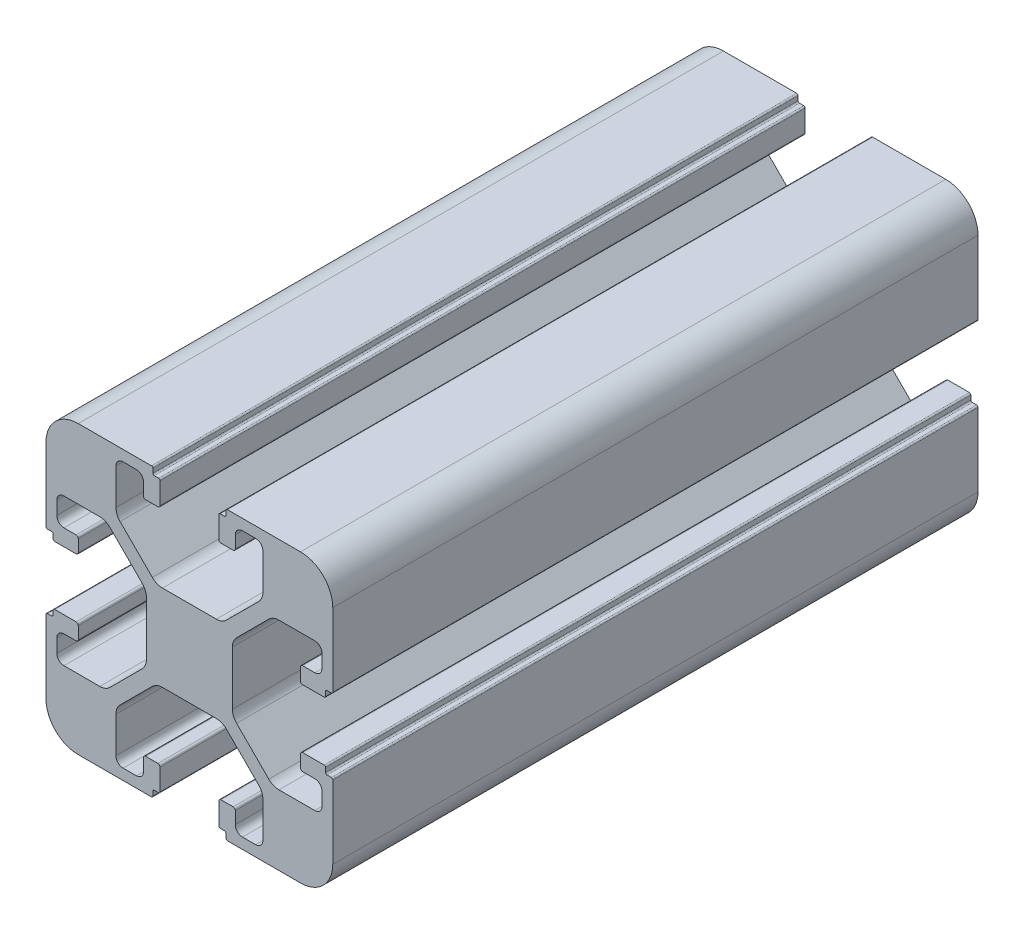
SolidWorks part; units mm, degrees
material "6063-T5"
ref_plane "Front Plane" through (0, 0, 0) normal (0, 0, 1) x (1, 0, 0)
ref_plane "Top Plane" through (0, 0, 0) normal (0, 1, 0) x (1, 0, 0)
ref_plane "Right Plane" through (0, 0, 0) normal (1, 0, 0) x (0, 0, -1)
sketch "Sketch2" plane through (0, 0, 0) normal (0, 0, 1) x (1, 0, 0)
  line L0 (4.5, 0) -> (14.7, 0)
  line L1 (40, 4.5) -> (40, 14.7)
  line L2 (35.5, 40) -> (25.3, 40)
  line L3 (0, 35.5) -> (0, 25.3)
  line L4 (15.9, 1.2) -> (15.9, 4.2)
  line L5 (24.1, 1.2) -> (24.1, 4.2)
  line L6 (38.8, 24.1) -> (35.8, 24.1)
  line L7 (35.5, 24.4) -> (35.5, 26.1)
  line L8 (14, 23.7574) -> (14, 16.2426)
  line L9 (16.2426, 14) -> (23.7574, 14)
  line L10 (26, 16.2426) -> (26, 23.7574)
  line L11 (13.4142, 14.8284) -> (8.9216, 10.3358)
  line L12 (23.7574, 26) -> (16.2426, 26)
  line L13 (4.5, 24.4) -> (4.5, 26.1)
  line L14 (1.2, 24.1) -> (4.2, 24.1)
  line L15 (15.9, 38.8) -> (15.9, 35.8)
  line L16 (14.8284, 26.5858) -> (10.3358, 31.0784)
  line L17 (13.4142, 25.1716) -> (8.9216, 29.6642)
  line L18 (14.8284, 13.4142) -> (10.3358, 8.9216)
  line L19 (25.1716, 13.4142) -> (29.6642, 8.9216)
  line L20 (26.5858, 14.8284) -> (31.0784, 10.3358)
  line L21 (26.5858, 25.1716) -> (31.0784, 29.6642)
  line L22 (25.1716, 26.5858) -> (29.6642, 31.0784)
  line L23 (24.1, 38.8) -> (24.1, 35.8)
  line L24 (14.7, 40) -> (4.5, 40)
  line L25 (25.3, 0) -> (35.5, 0)
  line L26 (38.8, 15.9) -> (35.8, 15.9)
  line L27 (40, 25.3) -> (40, 35.5)
  line L28 (1.2, 15.9) -> (4.2, 15.9)
  line L29 (0, 14.7) -> (0, 4.5)
  line L30 (4.5, 15.6) -> (4.5, 13.9)
  line L31 (35.5, 15.6) -> (35.5, 13.9)
  line L32 (15.6, 35.5) -> (13.9, 35.5)
  line L33 (24.4, 35.5) -> (26.1, 35.5)
  line L34 (15.6, 4.5) -> (13.9, 4.5)
  line L35 (24.4, 4.5) -> (26.1, 4.5)
  line L36 (12.6, 38.5) -> (10.75, 38.5)
  line L37 (1.5, 12.6) -> (1.5, 10.75)
  line L38 (27.4, 1.5) -> (29.25, 1.5)
  line L39 (38.5, 27.4) -> (38.5, 29.25)
  line L40 (38.5, 10.75) -> (38.5, 12.6)
  line L41 (29.25, 38.5) -> (27.4, 38.5)
  line L42 (1.5, 29.25) -> (1.5, 27.4)
  line L43 (10.75, 1.5) -> (12.6, 1.5)
  line L44 (35.8, 26.4) -> (37.5, 26.4)
  line L45 (35.8, 13.6) -> (37.5, 13.6)
  line L46 (4.2, 26.4) -> (2.5, 26.4)
  line L47 (13.6, 35.8) -> (13.6, 37.5)
  line L48 (26.4, 35.8) -> (26.4, 37.5)
  line L49 (4.2, 13.6) -> (2.5, 13.6)
  line L50 (13.6, 4.2) -> (13.6, 2.5)
  line L51 (26.4, 4.2) -> (26.4, 2.5)
  line L52 (9.75, 7.5074) -> (9.75, 2.5)
  line L53 (30.25, 7.5074) -> (30.25, 2.5)
  line L54 (9.75, 37.5) -> (9.75, 32.4926)
  line L55 (30.25, 37.5) -> (30.25, 32.4926)
  line L56 (32.4926, 30.25) -> (37.5, 30.25)
  line L57 (37.5, 9.75) -> (32.4926, 9.75)
  line L58 (2.5, 30.25) -> (7.5074, 30.25)
  line L59 (2.5, 9.75) -> (7.5074, 9.75)
  line L60 (31.55, 37.7) -> (31.55, 32.55)
  line L61 (32.55, 31.55) -> (37.7, 31.55)
  line L62 (1.3, 35.5) -> (1.3, 32.55)
  line L63 (4.5, 38.7) -> (7.45, 38.7)
  line L64 (32.55, 38.7) -> (35.5, 38.7)
  line L65 (38.7, 35.5) -> (38.7, 32.55)
  line L66 (8.45, 37.7) -> (8.45, 32.55)
  line L67 (2.3, 31.55) -> (7.45, 31.55)
  line L68 (1.3, 7.45) -> (1.3, 4.5)
  line L69 (2.3, 8.45) -> (7.45, 8.45)
  line L70 (8.45, 7.45) -> (8.45, 2.3)
  line L71 (4.5, 1.3) -> (7.45, 1.3)
  line L72 (31.55, 7.45) -> (31.55, 2.3)
  line L73 (32.55, 8.45) -> (37.7, 8.45)
  line L74 (38.7, 7.45) -> (38.7, 4.5)
  line L75 (32.55, 1.3) -> (35.5, 1.3)
  line L77 (14.9, 39.8) -> (14.9, 39.2)
  line L78 (15.1, 39) -> (15.7, 39)
  line L79 (25.1, 39.8) -> (25.1, 39.2)
  line L80 (24.9, 39) -> (24.3, 39)
  line L81 (25.1, 0.2) -> (25.1, 0.8)
  line L82 (24.9, 1) -> (24.3, 1)
  line L83 (14.9, 0.2) -> (14.9, 0.8)
  line L84 (15.1, 1) -> (15.7, 1)
  line L85 (0.2, 25.1) -> (0.8, 25.1)
  line L86 (1, 24.9) -> (1, 24.3)
  line L87 (0.2, 14.9) -> (0.8, 14.9)
  line L88 (1, 15.1) -> (1, 15.7)
  line L89 (39.8, 25.1) -> (39.2, 25.1)
  line L90 (39, 24.9) -> (39, 24.3)
  line L91 (39, 15.7) -> (39, 15.1)
  line L92 (39.2, 14.9) -> (39.8, 14.9)
  circle A0 centre (20, 20) radius 3.4
  arc A1 (1.3, 35.5) -> (4.5, 38.7) centre (4.5, 35.5) cw
  arc A2 (1.3, 4.5) -> (4.5, 1.3) centre (4.5, 4.5) ccw
  arc A3 (38.7, 4.5) -> (35.5, 1.3) centre (35.5, 4.5) cw
  arc A4 (35.5, 38.7) -> (38.7, 35.5) centre (35.5, 35.5) cw
  arc A5 (40, 35.5) -> (35.5, 40) centre (35.5, 35.5) ccw
  arc A6 (35.5, 0) -> (40, 4.5) centre (35.5, 4.5) ccw
  arc A7 (4.5, 0) -> (0, 4.5) centre (4.5, 4.5) cw
  arc A8 (4.5, 40) -> (0, 35.5) centre (4.5, 35.5) ccw
  arc A9 (13.4142, 14.8284) -> (14, 16.2426) centre (12, 16.2426) ccw
  arc A10 (7.5074, 9.75) -> (8.9216, 10.3358) centre (7.5074, 11.75) ccw
  arc A11 (9.75, 7.5074) -> (10.3358, 8.9216) centre (11.75, 7.5074) cw
  arc A12 (30.25, 7.5074) -> (29.6642, 8.9216) centre (28.25, 7.5074) ccw
  arc A13 (14.8284, 13.4142) -> (16.2426, 14) centre (16.2426, 12) cw
  arc A14 (25.1716, 13.4142) -> (23.7574, 14) centre (23.7574, 12) ccw
  arc A15 (32.4926, 9.75) -> (31.0784, 10.3358) centre (32.4926, 11.75) cw
  arc A16 (26.5858, 14.8284) -> (26, 16.2426) centre (28, 16.2426) cw
  arc A17 (32.4926, 30.25) -> (31.0784, 29.6642) centre (32.4926, 28.25) ccw
  arc A18 (26.5858, 25.1716) -> (26, 23.7574) centre (28, 23.7574) ccw
  arc A19 (13.4142, 25.1716) -> (14, 23.7574) centre (12, 23.7574) cw
  arc A20 (7.5074, 30.25) -> (8.9216, 29.6642) centre (7.5074, 28.25) cw
  arc A21 (9.75, 32.4926) -> (10.3358, 31.0784) centre (11.75, 32.4926) ccw
  arc A22 (30.25, 32.4926) -> (29.6642, 31.0784) centre (28.25, 32.4926) cw
  arc A23 (25.1716, 26.5858) -> (23.7574, 26) centre (23.7574, 28) cw
  arc A24 (14.8284, 26.5858) -> (16.2426, 26) centre (16.2426, 28) ccw
  arc A25 (37.7, 8.45) -> (38.7, 7.45) centre (37.7, 7.45) cw
  arc A26 (31.55, 2.3) -> (32.55, 1.3) centre (32.55, 2.3) ccw
  arc A27 (31.55, 7.45) -> (32.55, 8.45) centre (32.55, 7.45) cw
  arc A28 (8.45, 2.3) -> (7.45, 1.3) centre (7.45, 2.3) cw
  arc A29 (1.3, 7.45) -> (2.3, 8.45) centre (2.3, 7.45) cw
  arc A30 (7.45, 8.45) -> (8.45, 7.45) centre (7.45, 7.45) cw
  arc A31 (38.7, 32.55) -> (37.7, 31.55) centre (37.7, 32.55) cw
  arc A32 (31.55, 32.55) -> (32.55, 31.55) centre (32.55, 32.55) ccw
  arc A33 (31.55, 37.7) -> (32.55, 38.7) centre (32.55, 37.7) cw
  arc A34 (7.45, 38.7) -> (8.45, 37.7) centre (7.45, 37.7) cw
  arc A35 (8.45, 32.55) -> (7.45, 31.55) centre (7.45, 32.55) cw
  arc A36 (1.3, 32.55) -> (2.3, 31.55) centre (2.3, 32.55) ccw
  arc A37 (30.25, 2.5) -> (29.25, 1.5) centre (29.25, 2.5) cw
  arc A38 (26.4, 2.5) -> (27.4, 1.5) centre (27.4, 2.5) ccw
  arc A39 (13.6, 2.5) -> (12.6, 1.5) centre (12.6, 2.5) cw
  arc A40 (9.75, 2.5) -> (10.75, 1.5) centre (10.75, 2.5) ccw
  arc A41 (26.4, 37.5) -> (27.4, 38.5) centre (27.4, 37.5) cw
  arc A42 (30.25, 37.5) -> (29.25, 38.5) centre (29.25, 37.5) ccw
  arc A43 (37.5, 26.4) -> (38.5, 27.4) centre (37.5, 27.4) ccw
  arc A44 (37.5, 30.25) -> (38.5, 29.25) centre (37.5, 29.25) cw
  arc A45 (37.5, 13.6) -> (38.5, 12.6) centre (37.5, 12.6) cw
  arc A46 (37.5, 9.75) -> (38.5, 10.75) centre (37.5, 10.75) ccw
  arc A47 (2.5, 9.75) -> (1.5, 10.75) centre (2.5, 10.75) cw
  arc A48 (2.5, 13.6) -> (1.5, 12.6) centre (2.5, 12.6) ccw
  arc A49 (2.5, 26.4) -> (1.5, 27.4) centre (2.5, 27.4) cw
  arc A50 (2.5, 30.25) -> (1.5, 29.25) centre (2.5, 29.25) ccw
  arc A51 (9.75, 37.5) -> (10.75, 38.5) centre (10.75, 37.5) cw
  arc A52 (13.6, 37.5) -> (12.6, 38.5) centre (12.6, 37.5) ccw
  arc A53 (26.1, 35.5) -> (26.4, 35.8) centre (26.1, 35.8) ccw
  arc A54 (24.1, 35.8) -> (24.4, 35.5) centre (24.4, 35.8) ccw
  arc A55 (15.9, 35.8) -> (15.6, 35.5) centre (15.6, 35.8) cw
  arc A56 (13.9, 35.5) -> (13.6, 35.8) centre (13.9, 35.8) cw
  arc A57 (13.9, 4.5) -> (13.6, 4.2) centre (13.9, 4.2) ccw
  arc A58 (15.9, 4.2) -> (15.6, 4.5) centre (15.6, 4.2) ccw
  arc A59 (24.1, 4.2) -> (24.4, 4.5) centre (24.4, 4.2) cw
  arc A60 (26.1, 4.5) -> (26.4, 4.2) centre (26.1, 4.2) cw
  arc A61 (35.5, 13.9) -> (35.8, 13.6) centre (35.8, 13.9) ccw
  arc A62 (35.8, 15.9) -> (35.5, 15.6) centre (35.8, 15.6) ccw
  arc A63 (35.8, 24.1) -> (35.5, 24.4) centre (35.8, 24.4) cw
  arc A64 (35.5, 26.1) -> (35.8, 26.4) centre (35.8, 26.1) cw
  arc A65 (4.5, 13.9) -> (4.2, 13.6) centre (4.2, 13.9) cw
  arc A66 (4.2, 15.9) -> (4.5, 15.6) centre (4.2, 15.6) cw
  arc A67 (4.2, 24.1) -> (4.5, 24.4) centre (4.2, 24.4) ccw
  arc A68 (4.5, 26.1) -> (4.2, 26.4) centre (4.2, 26.1) ccw
  arc A69 (25.3, 0) -> (25.1, 0.2) centre (25.3, 0.2) cw
  arc A70 (25.1, 0.8) -> (24.9, 1) centre (24.9, 0.8) ccw
  arc A71 (24.3, 1) -> (24.1, 1.2) centre (24.3, 1.2) cw
  arc A72 (14.7, 0) -> (14.9, 0.2) centre (14.7, 0.2) ccw
  arc A73 (14.9, 0.8) -> (15.1, 1) centre (15.1, 0.8) cw
  arc A74 (15.7, 1) -> (15.9, 1.2) centre (15.7, 1.2) ccw
  arc A75 (39.8, 14.9) -> (40, 14.7) centre (39.8, 14.7) cw
  arc A76 (39, 15.1) -> (39.2, 14.9) centre (39.2, 15.1) ccw
  arc A77 (38.8, 15.9) -> (39, 15.7) centre (38.8, 15.7) cw
  arc A78 (0, 25.3) -> (0.2, 25.1) centre (0.2, 25.3) ccw
  arc A79 (0.8, 25.1) -> (1, 24.9) centre (0.8, 24.9) cw
  arc A80 (1, 24.3) -> (1.2, 24.1) centre (1.2, 24.3) ccw
  arc A81 (0, 14.7) -> (0.2, 14.9) centre (0.2, 14.7) cw
  arc A82 (0.8, 14.9) -> (1, 15.1) centre (0.8, 15.1) ccw
  arc A83 (1, 15.7) -> (1.2, 15.9) centre (1.2, 15.7) cw
  arc A84 (39, 24.3) -> (38.8, 24.1) centre (38.8, 24.3) cw
  arc A85 (39.2, 25.1) -> (39, 24.9) centre (39.2, 24.9) ccw
  arc A86 (40, 25.3) -> (39.8, 25.1) centre (39.8, 25.3) cw
  arc A87 (24.3, 39) -> (24.1, 38.8) centre (24.3, 38.8) ccw
  arc A88 (25.1, 39.2) -> (24.9, 39) centre (24.9, 39.2) cw
  arc A89 (25.3, 40) -> (25.1, 39.8) centre (25.3, 39.8) ccw
  arc A90 (14.9, 39.2) -> (15.1, 39) centre (15.1, 39.2) ccw
  arc A91 (15.7, 39) -> (15.9, 38.8) centre (15.7, 38.8) cw
  arc A92 (14.7, 40) -> (14.9, 39.8) centre (14.7, 39.8) cw
  point P93 (0, 0)
extrude "Boss-Extrude1" add sketch "Sketch2" along normal blind 50
sketch "Sketch3" plane through (0, 0, 50) normal (0, 0, 1) x (1, 0, 0)
  line L76 (25.3, 0) -> (35.5, 0)
  line L77 (40, 4.5) -> (40, 14.7)
  line L78 (39.8, 14.9) -> (39.2, 14.9)
  line L79 (39, 15.1) -> (39, 15.7)
  line L80 (38.8, 15.9) -> (35.8, 15.9)
  line L81 (35.5, 15.6) -> (35.5, 13.9)
  line L82 (35.8, 13.6) -> (37.5, 13.6)
  line L83 (38.5, 12.6) -> (38.5, 10.75)
  line L84 (37.5, 9.75) -> (32.4926, 9.75)
  line L85 (31.0784, 10.3358) -> (26.5858, 14.8284)
  line L86 (26, 16.2426) -> (26, 23.7574)
  line L87 (26.5858, 25.1716) -> (31.0784, 29.6642)
  line L88 (32.4926, 30.25) -> (37.5, 30.25)
  line L89 (38.5, 29.25) -> (38.5, 27.4)
  line L90 (37.5, 26.4) -> (35.8, 26.4)
  line L91 (35.5, 26.1) -> (35.5, 24.4)
  line L92 (35.8, 24.1) -> (38.8, 24.1)
  line L93 (39, 24.3) -> (39, 24.9)
  line L94 (39.2, 25.1) -> (39.8, 25.1)
  line L95 (40, 25.3) -> (40, 35.5)
  line L96 (35.5, 40) -> (25.3, 40)
  line L97 (25.1, 39.8) -> (25.1, 39.2)
  line L98 (24.9, 39) -> (24.3, 39)
  line L99 (24.1, 38.8) -> (24.1, 35.8)
  line L100 (24.4, 35.5) -> (26.1, 35.5)
  line L101 (26.4, 35.8) -> (26.4, 37.5)
  line L102 (27.4, 38.5) -> (29.25, 38.5)
  line L103 (30.25, 37.5) -> (30.25, 32.4926)
  line L104 (29.6642, 31.0784) -> (25.1716, 26.5858)
  line L105 (23.7574, 26) -> (16.2426, 26)
  line L106 (14.8284, 26.5858) -> (10.3358, 31.0784)
  line L107 (9.75, 32.4926) -> (9.75, 37.5)
  line L108 (10.75, 38.5) -> (12.6, 38.5)
  line L109 (13.6, 37.5) -> (13.6, 35.8)
  line L110 (13.9, 35.5) -> (15.6, 35.5)
  line L111 (15.9, 35.8) -> (15.9, 38.8)
  line L112 (15.7, 39) -> (15.1, 39)
  line L113 (14.9, 39.2) -> (14.9, 39.8)
  line L114 (14.7, 40) -> (4.5, 40)
  line L115 (0, 35.5) -> (0, 25.3)
  line L116 (0.2, 25.1) -> (0.8, 25.1)
  line L117 (1, 24.9) -> (1, 24.3)
  line L118 (1.2, 24.1) -> (4.2, 24.1)
  line L119 (4.5, 24.4) -> (4.5, 26.1)
  line L120 (4.2, 26.4) -> (2.5, 26.4)
  line L121 (1.5, 27.4) -> (1.5, 29.25)
  line L122 (2.5, 30.25) -> (7.5074, 30.25)
  line L123 (8.9216, 29.6642) -> (13.4142, 25.1716)
  line L124 (14, 23.7574) -> (14, 16.2426)
  line L125 (13.4142, 14.8284) -> (8.9216, 10.3358)
  line L126 (7.5074, 9.75) -> (2.5, 9.75)
  line L127 (1.5, 10.75) -> (1.5, 12.6)
  line L128 (2.5, 13.6) -> (4.2, 13.6)
  line L129 (4.5, 13.9) -> (4.5, 15.6)
  line L130 (4.2, 15.9) -> (1.2, 15.9)
  line L131 (1, 15.7) -> (1, 15.1)
  line L132 (0.8, 14.9) -> (0.2, 14.9)
  line L133 (0, 14.7) -> (0, 4.5)
  line L134 (4.5, 0) -> (14.7, 0)
  line L135 (14.9, 0.2) -> (14.9, 0.8)
  line L136 (15.1, 1) -> (15.7, 1)
  line L137 (15.9, 1.2) -> (15.9, 4.2)
  line L138 (15.6, 4.5) -> (13.9, 4.5)
  line L139 (13.6, 4.2) -> (13.6, 2.5)
  line L140 (12.6, 1.5) -> (10.75, 1.5)
  line L141 (9.75, 2.5) -> (9.75, 7.5074)
  line L142 (10.3358, 8.9216) -> (14.8284, 13.4142)
  line L143 (16.2426, 14) -> (23.7574, 14)
  line L144 (25.1716, 13.4142) -> (29.6642, 8.9216)
  line L145 (30.25, 7.5074) -> (30.25, 2.5)
  line L146 (29.25, 1.5) -> (27.4, 1.5)
  line L147 (26.4, 2.5) -> (26.4, 4.2)
  line L148 (26.1, 4.5) -> (24.4, 4.5)
  line L149 (24.1, 4.2) -> (24.1, 1.2)
  line L150 (24.3, 1) -> (24.9, 1)
  line L151 (25.1, 0.8) -> (25.1, 0.2)
  line L152 (25.3, 0) -> (35.5, 0)
  line L153 (40, 4.5) -> (40, 14.7)
  line L154 (39.8, 14.9) -> (39.2, 14.9)
  line L155 (39, 15.1) -> (39, 15.7)
  line L156 (38.8, 15.9) -> (35.8, 15.9)
  line L157 (35.5, 15.6) -> (35.5, 13.9)
  line L158 (35.8, 13.6) -> (37.5, 13.6)
  line L159 (38.5, 12.6) -> (38.5, 10.75)
  line L160 (37.5, 9.75) -> (32.4926, 9.75)
  line L161 (31.0784, 10.3358) -> (26.5858, 14.8284)
  line L162 (26, 16.2426) -> (26, 23.7574)
  line L163 (26.5858, 25.1716) -> (31.0784, 29.6642)
  line L164 (32.4926, 30.25) -> (37.5, 30.25)
  line L165 (38.5, 29.25) -> (38.5, 27.4)
  line L166 (37.5, 26.4) -> (35.8, 26.4)
  line L167 (35.5, 26.1) -> (35.5, 24.4)
  line L168 (35.8, 24.1) -> (38.8, 24.1)
  line L169 (39, 24.3) -> (39, 24.9)
  line L170 (39.2, 25.1) -> (39.8, 25.1)
  line L171 (40, 25.3) -> (40, 35.5)
  line L172 (35.5, 40) -> (25.3, 40)
  line L173 (25.1, 39.8) -> (25.1, 39.2)
  line L174 (24.9, 39) -> (24.3, 39)
  line L175 (24.1, 38.8) -> (24.1, 35.8)
  line L176 (24.4, 35.5) -> (26.1, 35.5)
  line L177 (26.4, 35.8) -> (26.4, 37.5)
  line L178 (27.4, 38.5) -> (29.25, 38.5)
  line L179 (30.25, 37.5) -> (30.25, 32.4926)
  line L180 (29.6642, 31.0784) -> (25.1716, 26.5858)
  line L181 (23.7574, 26) -> (16.2426, 26)
  line L182 (14.8284, 26.5858) -> (10.3358, 31.0784)
  line L183 (9.75, 32.4926) -> (9.75, 37.5)
  line L184 (10.75, 38.5) -> (12.6, 38.5)
  line L185 (13.6, 37.5) -> (13.6, 35.8)
  line L186 (13.9, 35.5) -> (15.6, 35.5)
  line L187 (15.9, 35.8) -> (15.9, 38.8)
  line L188 (15.7, 39) -> (15.1, 39)
  line L189 (14.9, 39.2) -> (14.9, 39.8)
  line L190 (14.7, 40) -> (4.5, 40)
  line L191 (0, 35.5) -> (0, 25.3)
  line L192 (0.2, 25.1) -> (0.8, 25.1)
  line L193 (1, 24.9) -> (1, 24.3)
  line L194 (1.2, 24.1) -> (4.2, 24.1)
  line L195 (4.5, 24.4) -> (4.5, 26.1)
  line L196 (4.2, 26.4) -> (2.5, 26.4)
  line L197 (1.5, 27.4) -> (1.5, 29.25)
  line L198 (2.5, 30.25) -> (7.5074, 30.25)
  line L199 (8.9216, 29.6642) -> (13.4142, 25.1716)
  line L200 (14, 23.7574) -> (14, 16.2426)
  line L201 (13.4142, 14.8284) -> (8.9216, 10.3358)
  line L202 (7.5074, 9.75) -> (2.5, 9.75)
  line L203 (1.5, 10.75) -> (1.5, 12.6)
  line L204 (2.5, 13.6) -> (4.2, 13.6)
  line L205 (4.5, 13.9) -> (4.5, 15.6)
  line L206 (4.2, 15.9) -> (1.2, 15.9)
  line L207 (1, 15.7) -> (1, 15.1)
  line L208 (0.8, 14.9) -> (0.2, 14.9)
  line L209 (0, 14.7) -> (0, 4.5)
  line L210 (4.5, 0) -> (14.7, 0)
  line L211 (14.9, 0.2) -> (14.9, 0.8)
  line L212 (15.1, 1) -> (15.7, 1)
  line L213 (15.9, 1.2) -> (15.9, 4.2)
  line L214 (15.6, 4.5) -> (13.9, 4.5)
  line L215 (13.6, 4.2) -> (13.6, 2.5)
  line L216 (12.6, 1.5) -> (10.75, 1.5)
  line L217 (9.75, 2.5) -> (9.75, 7.5074)
  line L218 (10.3358, 8.9216) -> (14.8284, 13.4142)
  line L219 (16.2426, 14) -> (23.7574, 14)
  line L220 (25.1716, 13.4142) -> (29.6642, 8.9216)
  line L221 (30.25, 7.5074) -> (30.25, 2.5)
  line L222 (29.25, 1.5) -> (27.4, 1.5)
  line L223 (26.4, 2.5) -> (26.4, 4.2)
  line L224 (26.1, 4.5) -> (24.4, 4.5)
  line L225 (24.1, 4.2) -> (24.1, 1.2)
  line L226 (24.3, 1) -> (24.9, 1)
  line L227 (25.1, 0.8) -> (25.1, 0.2)
  arc A76 (25.1, 0.2) -> (25.3, 0) centre (25.3, 0.2) ccw
  arc A77 (35.5, 0) -> (40, 4.5) centre (35.5, 4.5) ccw
  arc A78 (40, 14.7) -> (39.8, 14.9) centre (39.8, 14.7) ccw
  arc A79 (39, 15.1) -> (39.2, 14.9) centre (39.2, 15.1) ccw
  arc A80 (39, 15.7) -> (38.8, 15.9) centre (38.8, 15.7) ccw
  arc A81 (35.8, 15.9) -> (35.5, 15.6) centre (35.8, 15.6) ccw
  arc A82 (35.5, 13.9) -> (35.8, 13.6) centre (35.8, 13.9) ccw
  arc A83 (38.5, 12.6) -> (37.5, 13.6) centre (37.5, 12.6) ccw
  arc A84 (37.5, 9.75) -> (38.5, 10.75) centre (37.5, 10.75) ccw
  arc A85 (31.0784, 10.3358) -> (32.4926, 9.75) centre (32.4926, 11.75) ccw
  arc A86 (26, 16.2426) -> (26.5858, 14.8284) centre (28, 16.2426) ccw
  arc A87 (26.5858, 25.1716) -> (26, 23.7574) centre (28, 23.7574) ccw
  arc A88 (32.4926, 30.25) -> (31.0784, 29.6642) centre (32.4926, 28.25) ccw
  arc A89 (38.5, 29.25) -> (37.5, 30.25) centre (37.5, 29.25) ccw
  arc A90 (37.5, 26.4) -> (38.5, 27.4) centre (37.5, 27.4) ccw
  arc A91 (35.8, 26.4) -> (35.5, 26.1) centre (35.8, 26.1) ccw
  arc A92 (35.5, 24.4) -> (35.8, 24.1) centre (35.8, 24.4) ccw
  arc A93 (38.8, 24.1) -> (39, 24.3) centre (38.8, 24.3) ccw
  arc A94 (39.2, 25.1) -> (39, 24.9) centre (39.2, 24.9) ccw
  arc A95 (39.8, 25.1) -> (40, 25.3) centre (39.8, 25.3) ccw
  arc A96 (40, 35.5) -> (35.5, 40) centre (35.5, 35.5) ccw
  arc A97 (25.3, 40) -> (25.1, 39.8) centre (25.3, 39.8) ccw
  arc A98 (24.9, 39) -> (25.1, 39.2) centre (24.9, 39.2) ccw
  arc A99 (24.3, 39) -> (24.1, 38.8) centre (24.3, 38.8) ccw
  arc A100 (24.1, 35.8) -> (24.4, 35.5) centre (24.4, 35.8) ccw
  arc A101 (26.1, 35.5) -> (26.4, 35.8) centre (26.1, 35.8) ccw
  arc A102 (27.4, 38.5) -> (26.4, 37.5) centre (27.4, 37.5) ccw
  arc A103 (30.25, 37.5) -> (29.25, 38.5) centre (29.25, 37.5) ccw
  arc A104 (29.6642, 31.0784) -> (30.25, 32.4926) centre (28.25, 32.4926) ccw
  arc A105 (23.7574, 26) -> (25.1716, 26.5858) centre (23.7574, 28) ccw
  arc A106 (14.8284, 26.5858) -> (16.2426, 26) centre (16.2426, 28) ccw
  arc A107 (9.75, 32.4926) -> (10.3358, 31.0784) centre (11.75, 32.4926) ccw
  arc A108 (10.75, 38.5) -> (9.75, 37.5) centre (10.75, 37.5) ccw
  arc A109 (13.6, 37.5) -> (12.6, 38.5) centre (12.6, 37.5) ccw
  arc A110 (13.6, 35.8) -> (13.9, 35.5) centre (13.9, 35.8) ccw
  arc A111 (15.6, 35.5) -> (15.9, 35.8) centre (15.6, 35.8) ccw
  arc A112 (15.9, 38.8) -> (15.7, 39) centre (15.7, 38.8) ccw
  arc A113 (14.9, 39.2) -> (15.1, 39) centre (15.1, 39.2) ccw
  arc A114 (14.9, 39.8) -> (14.7, 40) centre (14.7, 39.8) ccw
  arc A115 (4.5, 40) -> (0, 35.5) centre (4.5, 35.5) ccw
  arc A116 (0, 25.3) -> (0.2, 25.1) centre (0.2, 25.3) ccw
  arc A117 (1, 24.9) -> (0.8, 25.1) centre (0.8, 24.9) ccw
  arc A118 (1, 24.3) -> (1.2, 24.1) centre (1.2, 24.3) ccw
  arc A119 (4.2, 24.1) -> (4.5, 24.4) centre (4.2, 24.4) ccw
  arc A120 (4.5, 26.1) -> (4.2, 26.4) centre (4.2, 26.1) ccw
  arc A121 (1.5, 27.4) -> (2.5, 26.4) centre (2.5, 27.4) ccw
  arc A122 (2.5, 30.25) -> (1.5, 29.25) centre (2.5, 29.25) ccw
  arc A123 (8.9216, 29.6642) -> (7.5074, 30.25) centre (7.5074, 28.25) ccw
  arc A124 (14, 23.7574) -> (13.4142, 25.1716) centre (12, 23.7574) ccw
  arc A125 (13.4142, 14.8284) -> (14, 16.2426) centre (12, 16.2426) ccw
  arc A126 (7.5074, 9.75) -> (8.9216, 10.3358) centre (7.5074, 11.75) ccw
  arc A127 (1.5, 10.75) -> (2.5, 9.75) centre (2.5, 10.75) ccw
  arc A128 (2.5, 13.6) -> (1.5, 12.6) centre (2.5, 12.6) ccw
  arc A129 (4.2, 13.6) -> (4.5, 13.9) centre (4.2, 13.9) ccw
  arc A130 (4.5, 15.6) -> (4.2, 15.9) centre (4.2, 15.6) ccw
  arc A131 (1.2, 15.9) -> (1, 15.7) centre (1.2, 15.7) ccw
  arc A132 (0.8, 14.9) -> (1, 15.1) centre (0.8, 15.1) ccw
  arc A133 (0.2, 14.9) -> (0, 14.7) centre (0.2, 14.7) ccw
  arc A134 (0, 4.5) -> (4.5, 0) centre (4.5, 4.5) ccw
  arc A135 (14.7, 0) -> (14.9, 0.2) centre (14.7, 0.2) ccw
  arc A136 (15.1, 1) -> (14.9, 0.8) centre (15.1, 0.8) ccw
  arc A137 (15.7, 1) -> (15.9, 1.2) centre (15.7, 1.2) ccw
  arc A138 (15.9, 4.2) -> (15.6, 4.5) centre (15.6, 4.2) ccw
  arc A139 (13.9, 4.5) -> (13.6, 4.2) centre (13.9, 4.2) ccw
  arc A140 (12.6, 1.5) -> (13.6, 2.5) centre (12.6, 2.5) ccw
  arc A141 (9.75, 2.5) -> (10.75, 1.5) centre (10.75, 2.5) ccw
  arc A142 (10.3358, 8.9216) -> (9.75, 7.5074) centre (11.75, 7.5074) ccw
  arc A143 (16.2426, 14) -> (14.8284, 13.4142) centre (16.2426, 12) ccw
  arc A144 (25.1716, 13.4142) -> (23.7574, 14) centre (23.7574, 12) ccw
  arc A145 (30.25, 7.5074) -> (29.6642, 8.9216) centre (28.25, 7.5074) ccw
  arc A146 (29.25, 1.5) -> (30.25, 2.5) centre (29.25, 2.5) ccw
  arc A147 (26.4, 2.5) -> (27.4, 1.5) centre (27.4, 2.5) ccw
  arc A148 (26.4, 4.2) -> (26.1, 4.5) centre (26.1, 4.2) ccw
  arc A149 (24.4, 4.5) -> (24.1, 4.2) centre (24.4, 4.2) ccw
  arc A150 (24.1, 1.2) -> (24.3, 1) centre (24.3, 1.2) ccw
  arc A151 (25.1, 0.8) -> (24.9, 1) centre (24.9, 0.8) ccw
  arc A152 (25.1, 0.2) -> (25.3, 0) centre (25.3, 0.2) ccw
  arc A153 (35.5, 0) -> (40, 4.5) centre (35.5, 4.5) ccw
  arc A154 (40, 14.7) -> (39.8, 14.9) centre (39.8, 14.7) ccw
  arc A155 (39, 15.1) -> (39.2, 14.9) centre (39.2, 15.1) ccw
  arc A156 (39, 15.7) -> (38.8, 15.9) centre (38.8, 15.7) ccw
  arc A157 (35.8, 15.9) -> (35.5, 15.6) centre (35.8, 15.6) ccw
  arc A158 (35.5, 13.9) -> (35.8, 13.6) centre (35.8, 13.9) ccw
  arc A159 (38.5, 12.6) -> (37.5, 13.6) centre (37.5, 12.6) ccw
  arc A160 (37.5, 9.75) -> (38.5, 10.75) centre (37.5, 10.75) ccw
  arc A161 (31.0784, 10.3358) -> (32.4926, 9.75) centre (32.4926, 11.75) ccw
  arc A162 (26, 16.2426) -> (26.5858, 14.8284) centre (28, 16.2426) ccw
  arc A163 (26.5858, 25.1716) -> (26, 23.7574) centre (28, 23.7574) ccw
  arc A164 (32.4926, 30.25) -> (31.0784, 29.6642) centre (32.4926, 28.25) ccw
  arc A165 (38.5, 29.25) -> (37.5, 30.25) centre (37.5, 29.25) ccw
  arc A166 (37.5, 26.4) -> (38.5, 27.4) centre (37.5, 27.4) ccw
  arc A167 (35.8, 26.4) -> (35.5, 26.1) centre (35.8, 26.1) ccw
  arc A168 (35.5, 24.4) -> (35.8, 24.1) centre (35.8, 24.4) ccw
  arc A169 (38.8, 24.1) -> (39, 24.3) centre (38.8, 24.3) ccw
  arc A170 (39.2, 25.1) -> (39, 24.9) centre (39.2, 24.9) ccw
  arc A171 (39.8, 25.1) -> (40, 25.3) centre (39.8, 25.3) ccw
  arc A172 (40, 35.5) -> (35.5, 40) centre (35.5, 35.5) ccw
  arc A173 (25.3, 40) -> (25.1, 39.8) centre (25.3, 39.8) ccw
  arc A174 (24.9, 39) -> (25.1, 39.2) centre (24.9, 39.2) ccw
  arc A175 (24.3, 39) -> (24.1, 38.8) centre (24.3, 38.8) ccw
  arc A176 (24.1, 35.8) -> (24.4, 35.5) centre (24.4, 35.8) ccw
  arc A177 (26.1, 35.5) -> (26.4, 35.8) centre (26.1, 35.8) ccw
  arc A178 (27.4, 38.5) -> (26.4, 37.5) centre (27.4, 37.5) ccw
  arc A179 (30.25, 37.5) -> (29.25, 38.5) centre (29.25, 37.5) ccw
  arc A180 (29.6642, 31.0784) -> (30.25, 32.4926) centre (28.25, 32.4926) ccw
  arc A181 (23.7574, 26) -> (25.1716, 26.5858) centre (23.7574, 28) ccw
  arc A182 (14.8284, 26.5858) -> (16.2426, 26) centre (16.2426, 28) ccw
  arc A183 (9.75, 32.4926) -> (10.3358, 31.0784) centre (11.75, 32.4926) ccw
  arc A184 (10.75, 38.5) -> (9.75, 37.5) centre (10.75, 37.5) ccw
  arc A185 (13.6, 37.5) -> (12.6, 38.5) centre (12.6, 37.5) ccw
  arc A186 (13.6, 35.8) -> (13.9, 35.5) centre (13.9, 35.8) ccw
  arc A187 (15.6, 35.5) -> (15.9, 35.8) centre (15.6, 35.8) ccw
  arc A188 (15.9, 38.8) -> (15.7, 39) centre (15.7, 38.8) ccw
  arc A189 (14.9, 39.2) -> (15.1, 39) centre (15.1, 39.2) ccw
  arc A190 (14.9, 39.8) -> (14.7, 40) centre (14.7, 39.8) ccw
  arc A191 (4.5, 40) -> (0, 35.5) centre (4.5, 35.5) ccw
  arc A192 (0, 25.3) -> (0.2, 25.1) centre (0.2, 25.3) ccw
  arc A193 (1, 24.9) -> (0.8, 25.1) centre (0.8, 24.9) ccw
  arc A194 (1, 24.3) -> (1.2, 24.1) centre (1.2, 24.3) ccw
  arc A195 (4.2, 24.1) -> (4.5, 24.4) centre (4.2, 24.4) ccw
  arc A196 (4.5, 26.1) -> (4.2, 26.4) centre (4.2, 26.1) ccw
  arc A197 (1.5, 27.4) -> (2.5, 26.4) centre (2.5, 27.4) ccw
  arc A198 (2.5, 30.25) -> (1.5, 29.25) centre (2.5, 29.25) ccw
  arc A199 (8.9216, 29.6642) -> (7.5074, 30.25) centre (7.5074, 28.25) ccw
  arc A200 (14, 23.7574) -> (13.4142, 25.1716) centre (12, 23.7574) ccw
  arc A201 (13.4142, 14.8284) -> (14, 16.2426) centre (12, 16.2426) ccw
  arc A202 (7.5074, 9.75) -> (8.9216, 10.3358) centre (7.5074, 11.75) ccw
  arc A203 (1.5, 10.75) -> (2.5, 9.75) centre (2.5, 10.75) ccw
  arc A204 (2.5, 13.6) -> (1.5, 12.6) centre (2.5, 12.6) ccw
  arc A205 (4.2, 13.6) -> (4.5, 13.9) centre (4.2, 13.9) ccw
  arc A206 (4.5, 15.6) -> (4.2, 15.9) centre (4.2, 15.6) ccw
  arc A207 (1.2, 15.9) -> (1, 15.7) centre (1.2, 15.7) ccw
  arc A208 (0.8, 14.9) -> (1, 15.1) centre (0.8, 15.1) ccw
  arc A209 (0.2, 14.9) -> (0, 14.7) centre (0.2, 14.7) ccw
  arc A210 (0, 4.5) -> (4.5, 0) centre (4.5, 4.5) ccw
  arc A211 (14.7, 0) -> (14.9, 0.2) centre (14.7, 0.2) ccw
  arc A212 (15.1, 1) -> (14.9, 0.8) centre (15.1, 0.8) ccw
  arc A213 (15.7, 1) -> (15.9, 1.2) centre (15.7, 1.2) ccw
  arc A214 (15.9, 4.2) -> (15.6, 4.5) centre (15.6, 4.2) ccw
  arc A215 (13.9, 4.5) -> (13.6, 4.2) centre (13.9, 4.2) ccw
  arc A216 (12.6, 1.5) -> (13.6, 2.5) centre (12.6, 2.5) ccw
  arc A217 (9.75, 2.5) -> (10.75, 1.5) centre (10.75, 2.5) ccw
  arc A218 (10.3358, 8.9216) -> (9.75, 7.5074) centre (11.75, 7.5074) ccw
  arc A219 (16.2426, 14) -> (14.8284, 13.4142) centre (16.2426, 12) ccw
  arc A220 (25.1716, 13.4142) -> (23.7574, 14) centre (23.7574, 12) ccw
  arc A221 (30.25, 7.5074) -> (29.6642, 8.9216) centre (28.25, 7.5074) ccw
  arc A222 (29.25, 1.5) -> (30.25, 2.5) centre (29.25, 2.5) ccw
  arc A223 (26.4, 2.5) -> (27.4, 1.5) centre (27.4, 2.5) ccw
  arc A224 (26.4, 4.2) -> (26.1, 4.5) centre (26.1, 4.2) ccw
  arc A225 (24.4, 4.5) -> (24.1, 4.2) centre (24.4, 4.2) ccw
  arc A226 (24.1, 1.2) -> (24.3, 1) centre (24.3, 1.2) ccw
  arc A227 (25.1, 0.8) -> (24.9, 1) centre (24.9, 0.8) ccw
  dimension "D1" = 0
extrude "Boss-Extrude2" add sketch "Sketch3" along normal blind 40
